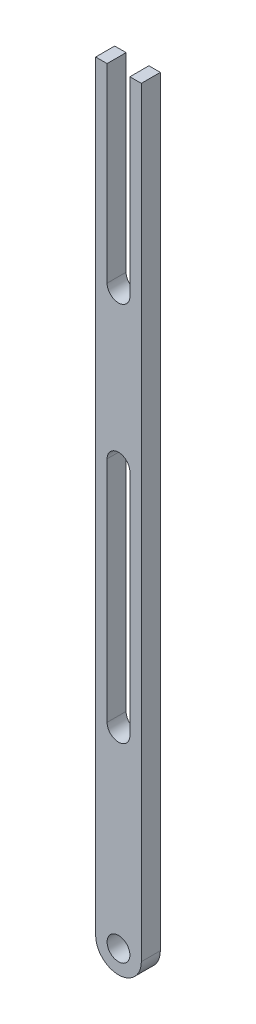
SolidWorks part; units mm, degrees
ref_plane "Front Plane" through (0, 0, 0) normal (0, 0, 1) x (1, 0, 0)
ref_plane "Top Plane" through (0, 0, 0) normal (0, 1, 0) x (1, 0, 0)
ref_plane "Right Plane" through (0, 0, 0) normal (1, 0, 0) x (0, 0, -1)
sketch "Sketch1" plane through (0, 0, 0) normal (0, 0, 1) x (1, 0, 0)
  line L2 (-0.6, -8) -> (-0.6, 192)
  line L3 (-0.6, 192) -> (11.4, 192)
  line L4 (11.4, 192) -> (11.4, -8)
  arc A1 (11.4, -8) -> (-0.6, -8) centre (5.4, -8) cw
extrude "Boss-Extrude1" add sketch "Sketch1" along normal blind 5
sketch "Sketch2" plane through (0, 0, 5) normal (0, 0, 1) x (1, 0, 0)
  circle A0 centre (5.4, -8) radius 3
extrude "Cut-Extrude1" cut sketch "Sketch2" against normal blind 5
sketch "Sketch4" plane through (0, 0, 5) normal (0, 0, 1) x (1, 0, 0)
  line L2 (2.4, 102) -> (2.4, 42)
  line L3 (8.4, 42) -> (8.4, 102)
  arc A0 (8.4, 102) -> (2.4, 102) centre (5.4, 102) ccw
  arc A1 (2.4, 42) -> (8.4, 42) centre (5.4, 42) ccw
extrude "Cut-Extrude2" cut sketch "Sketch4" against normal blind 5
sketch "Sketch5" plane through (0, 0, 5) normal (0, 0, 1) x (1, 0, 0)
  line L0 (2.4, 192) -> (2.4, 142)
  line L1 (11.4, 192) -> (-0.6, 192) construction
  line L3 (8.4, 142) -> (8.4, 192)
  line L4 (2.4, 192) -> (8.4, 192)
  arc A0 (8.4, 142) -> (2.4, 142) centre (5.4, 142) cw
extrude "Cut-Extrude7" cut sketch "Sketch5" against normal blind 5
